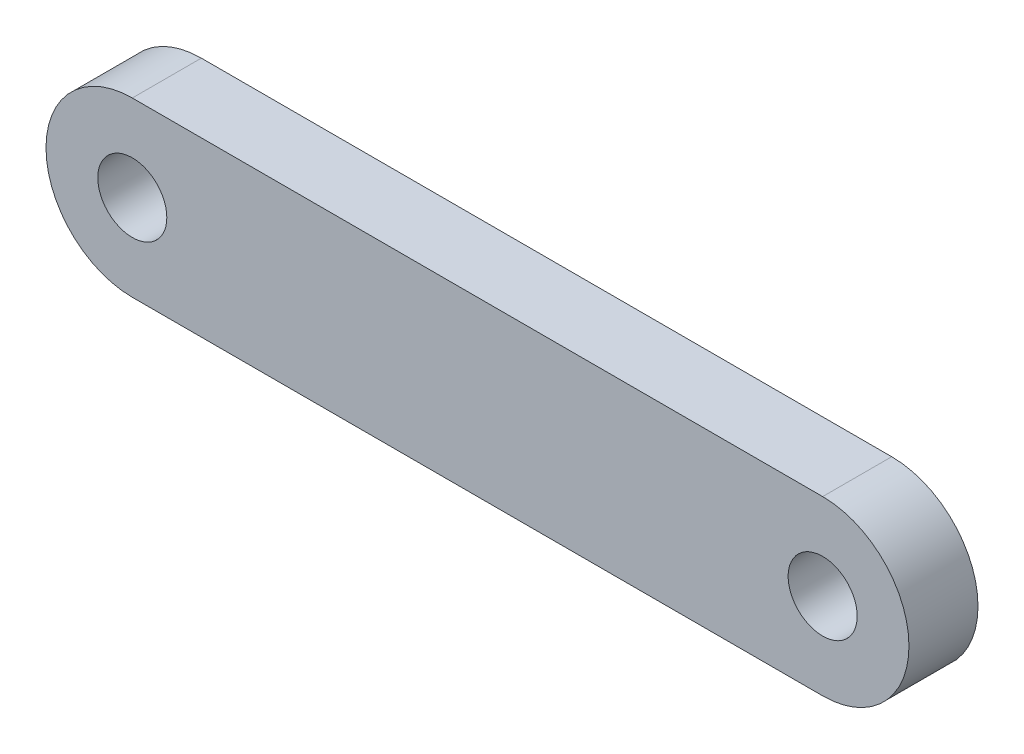
SolidWorks part; units mm, degrees
ref_plane "Plan de face" through (0, 0, 0) normal (0, 0, 1) x (1, 0, 0)
ref_plane "Plan de dessus" through (0, 0, 0) normal (0, 1, 0) x (1, 0, 0)
ref_plane "Plan de droite" through (0, 0, 0) normal (1, 0, 0) x (0, 0, -1)
sketch "Esquisse1" plane through (0, 0, 0) normal (0, 0, 1) x (1, 0, 0)
  line L0 (0, 0) -> (40, 0) construction
  line L1 (0, 5) -> (40, 5)
  line L2 (0, -5) -> (40, -5)
  arc A0 (0, 5) -> (0, -5) centre (0, 0) ccw
  arc A1 (40, -5) -> (40, 5) centre (40, 0) ccw
  circle A2 centre (40, 0) radius 2
  circle A3 centre (0, 0) radius 2
  point P3 (20, 0)
  point P8 (-5, 0)
  point P9 (45, 0)
  dimension "D2" = 5
  dimension "D3" = 4
  dimension "D4" = 4
  dimension "D1" = 50
extrude "Boss.-Extru.1" add sketch "Esquisse1" along normal blind 4
